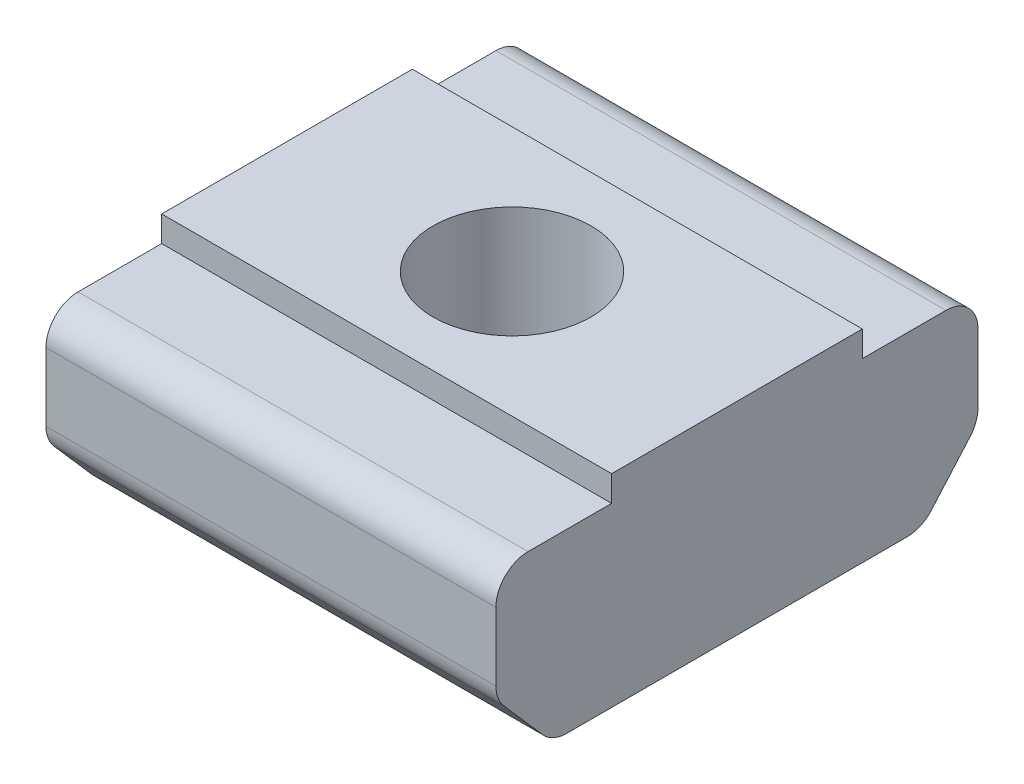
SolidWorks part; units mm, degrees
ref_plane "Front Plane" through (0, 0, 0) normal (0, 0, 1) x (1, 0, 0)
ref_plane "Top Plane" through (0, 0, 0) normal (0, 1, 0) x (1, 0, 0)
ref_plane "Right Plane" through (0, 0, 0) normal (1, 0, 0) x (0, 0, -1)
ref_plane "Plane1" through (-7, 0, 0) normal (1, 0, 0) x (0, 0, -1)
ref_plane "Plane2" through (-4.2, 0, 0) normal (1, 0, 0) x (0, 0, -1)
sketch "Axis_Line_X" plane through (0, 0, 0) normal (0, 1, 0) x (1, 0, 0)
  line L0 (0, 0) -> (50, 0)
  dimension "FIX_3" = 50
sketch "Axis_Line_Z" plane through (0, 0, 0) normal (0, 1, 0) x (1, 0, 0)
  line L0 (0, 0) -> (0, -50)
  dimension "FIX_4" = 50
sketch "Sketch1" plane through (-7, 0, 0) normal (1, 0, 0) x (0, 0, -1)
  line L0 (5.75, -6.3) -> (-5.75, -6.3)
  line L1 (-7.5, -0.8) -> (-7.5, -4.3)
  line L2 (-7.5, -0.8) -> (-3.9, -0.8)
  line L3 (-3.9, -0.8) -> (-3.9, 0)
  line L4 (-3.9, 0) -> (3.9, 0)
  line L5 (3.9, 0) -> (3.9, -0.8)
  line L6 (3.9, -0.8) -> (7.5, -0.8)
  line L7 (7.5, -0.8) -> (7.5, -4.3)
  line L8 (7.5, -4.3) -> (5.75, -6.3)
  line L9 (0, 0) -> (0, -6.3) construction
  line L10 (-7.5, -4.3) -> (-5.75, -6.3)
  point P15 (-7.5, -0.8)
  point P18 (-7.5, -4.3)
  point P21 (-5.75, -6.3)
  point P24 (5.75, -6.3)
  point P27 (7.5, -4.3)
  point P30 (7.5, -0.8)
  dimension "FIX_8" = 5.5
  dimension "FIX_6" = 7.8
  dimension "FIX_7" = 6.3
  dimension "FIX_9" = 3.5
  dimension "FIX_5" = 15
  dimension "FIX_10" = 11.5
extrude "Boss-Extrude1" add sketch "Sketch1" along normal blind 14
fillet "Fillet1" radius 1 6 edges at (0, -0.8, 7.5) (0, -4.3, 7.5) (0, -6.3, 5.75) (0, -6.3, -5.75) (0, -4.3, -7.5) (0, -0.8, -7.5)
hole_wizard "Tapped Hole1" positions "Sketch3" profile "Sketch2" tap size "M6x1.0" standard "JIS" end condition through all
sketch "Sketch3" plane through (0, 0, 0) normal (0, 1, 0) x (1, 0, 0)
  point P0 (0, 0)
sketch "Sketch2" plane through (0, 0, 0) normal (1, 0, 0) x (0, 0, 1)
  line L0 (0, 0) -> (0, 6.3)
  line L1 (0, 6.3) -> (2.4585, 6.3)
  line L2 (2.4585, 6.3) -> (2.4585, 0)
  line L5 (2.4585, 0) -> (0, 0)
  line L11 (0, 0) -> (0, 6.3) construction
  dimension "Thru Tap Drill Dia." = 4.917
  dimension "Thru Tap Drill Depth" = 6.3
cosmetic thread "Thread1"
sketch "Sketch4" [suppressed] plane through (-4.2, 0, 0) normal (1, 0, 0) x (0, 0, -1)
  line L0 (6.1, -0.75) -> (6.1, -0.8)
  line L1 (6.1, -0.8) -> (6.15, -0.8)
  line L2 (6.1, -0.75) -> (6.1, -0.8) construction
  arc A0 (6.15, -0.8) -> (6.1, -0.75) centre (6.1, -0.8) ccw
  dimension "FIX_14" = 0.1
  dimension "FIX_13" = 0.8
  dimension "FIX_12" = 6.1
revolve "Revolve1" [suppressed] add sketch "Sketch4" angle 360 about L2
pattern_linear "LPattern1" [suppressed]
